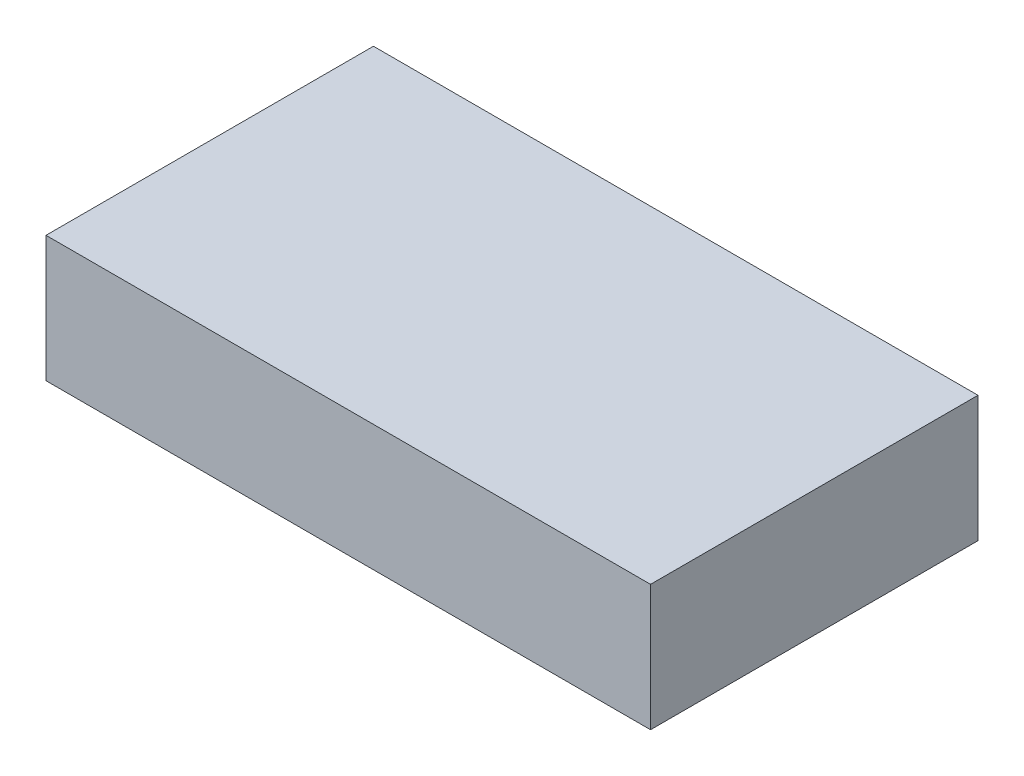
SolidWorks part; units mm, degrees
ref_plane "Front Plane" through (0, 0, 0) normal (0, 0, 1) x (1, 0, 0)
ref_plane "Top Plane" through (0, 0, 0) normal (0, 1, 0) x (1, 0, 0)
ref_plane "Right Plane" through (0, 0, 0) normal (1, 0, 0) x (0, 0, -1)
sketch "Sketch1" plane through (0, 0, 0) normal (0, 1, 0) x (1, 0, 0)
  line L1 (-12, -6.5) -> (12, -6.5)
  line L2 (-12, -6.5) -> (-12, 6.5)
  line L3 (-12, 6.5) -> (12, 6.5)
  line L4 (12, -6.5) -> (12, 6.5)
  line L5 (-12, -6.5) -> (12, 6.5) construction
  line L6 (-12, 6.5) -> (12, -6.5) construction
  point P0 (0, 0)
  dimension "D1" = 24
  dimension "D2" = 13
extrude "Boss-Extrude1" add sketch "Sketch1" along normal mid plane 5
